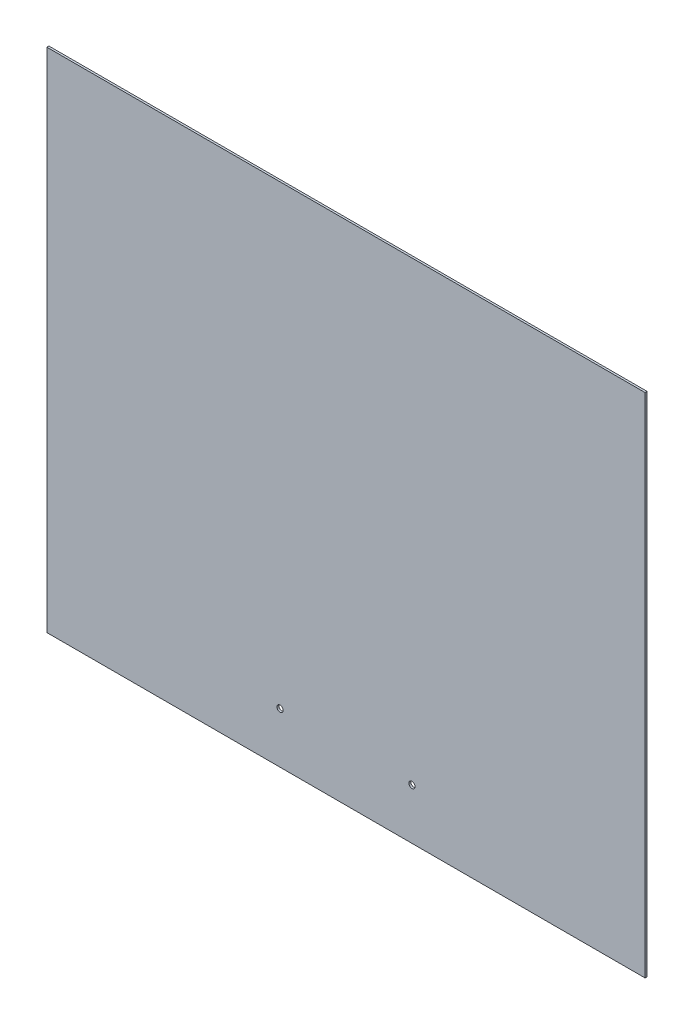
SolidWorks part; units mm, degrees
ref_plane "Front Plane" through (0, 0, 0) normal (0, 0, 1) x (1, 0, 0)
ref_plane "Top Plane" through (0, 0, 0) normal (0, 1, 0) x (1, 0, 0)
ref_plane "Right Plane" through (0, 0, 0) normal (1, 0, 0) x (0, 0, -1)
sketch "Sketch1" plane through (0, 0, 0) normal (0, 0, 1) x (1, 0, 0)
  line L1 (0, 0) -> (590, 0)
  line L2 (0, 0) -> (0, -500)
  line L3 (0, -500) -> (590, -500)
  line L4 (590, 0) -> (590, -500)
  dimension "D1" = 590
  dimension "D2" = 500
extrude "Boss-Extrude1" add sketch "Sketch1" along normal blind 2
sketch "Sketch2" plane through (0, 0, 2) normal (0, 0, 1) x (1, 0, 0)
  line L0 (295, 0) -> (295, -500) construction
  line L1 (590, 0) -> (0, 0) construction
  line L2 (0, -500) -> (590, -500) construction
  line L3 (230, -450) -> (360, -450) construction
  circle A0 centre (230, -450) radius 3.1
  circle A1 centre (360, -450) radius 3.1
  point P10 (0, 0)
  dimension "D1" = 6.2
  dimension "D2" = 50
  dimension "D3" = 130
extrude "Cut-Extrude1" cut sketch "Sketch2" against normal through all
